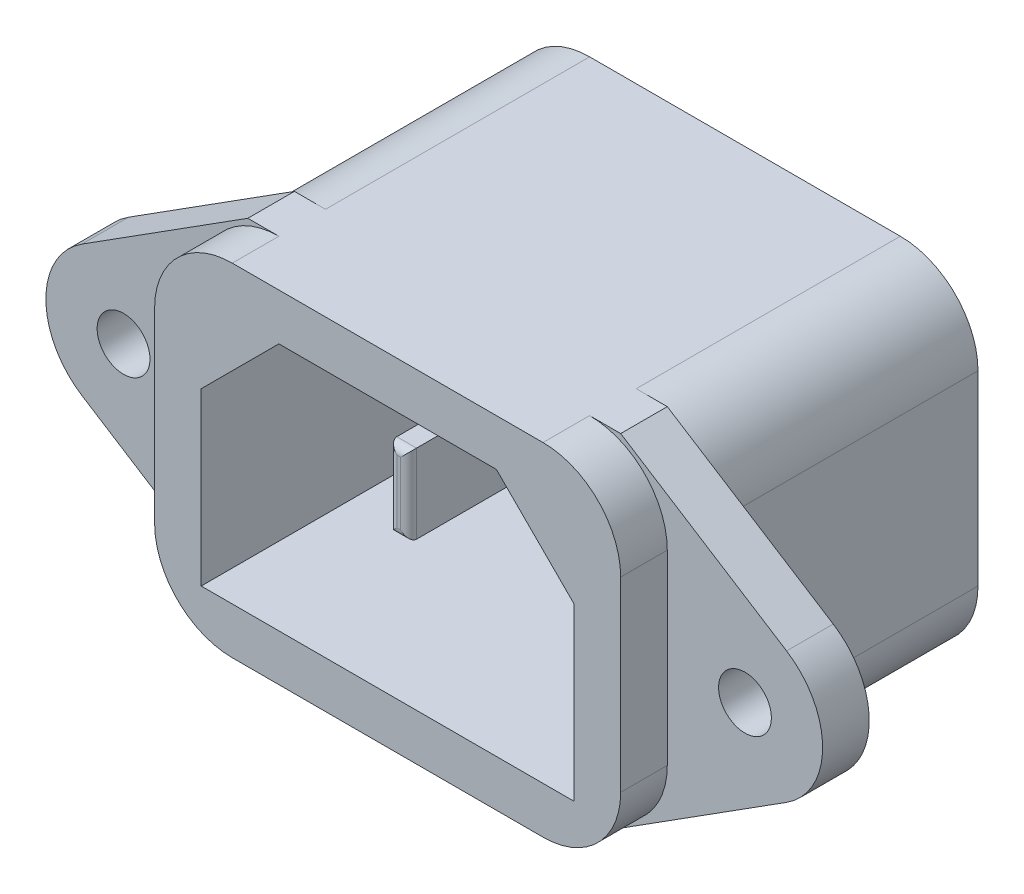
SolidWorks part; units mm, degrees
ref_plane "Front Plane" through (0, 0, 0) normal (0, 0, 1) x (1, 0, 0)
ref_plane "Top Plane" through (0, 0, 0) normal (0, 1, 0) x (1, 0, 0)
ref_plane "Right Plane" through (0, 0, 0) normal (1, 0, 0) x (0, 0, -1)
sketch "Sketch1" plane through (0, 0, 0) normal (0, 0, 1) x (1, 0, 0)
  line L0 (24, 22) -> (34.6795, 15.2214)
  line L1 (0, 0) -> (24, 0)
  line L3 (0, 22) -> (24, 22)
  line L5 (34.6795, 6.7786) -> (24, 0)
  line L6 (0, 22) -> (-10.6795, 15.2214)
  line L7 (-10.6795, 6.7786) -> (0, 0)
  arc A0 (34.6795, 15.2214) -> (34.6795, 6.7786) centre (32, 11) cw
  arc A1 (-10.6795, 15.2214) -> (-10.6795, 6.7786) centre (-8, 11) ccw
  point P9 (41.3302, 11)
  point P12 (-17.3302, 11)
  point P13 (12, 22)
  dimension "D5" = 5
  dimension "D6" = 5
  dimension "D1" = 24
  dimension "D2" = 22
  dimension "D3" = 20
  dimension "D4" = 20
extrude "Boss-Extrude1" add sketch "Sketch1" along normal blind 3
sketch "Sketch2" plane through (0, 0, 3) normal (0, 0, 1) x (1, 0, 0)
  circle A0 centre (32, 11) radius 1.7
  circle A1 centre (-8, 11) radius 1.7
  dimension "D1" = 3.4
  dimension "D2" = 3.4
extrude "Cut-Extrude1" cut sketch "Sketch2" against normal blind 3
sketch "Sketch3" plane through (0, 0, 3) normal (0, 0, 1) x (1, 0, 0)
  line L1 (2, 22) -> (22, 22)
  line L2 (-3, 17) -> (-3, 5)
  line L3 (2, 0) -> (22, 0)
  line L4 (27, 17) -> (27, 5)
  circle A0 centre (32, 11) radius 1.7 construction
  circle A4 centre (-8, 11) radius 1.7 construction
  arc A5 (-3, 5) -> (2, 0) centre (2, 5) ccw
  arc A6 (22, 0) -> (27, 5) centre (22, 5) ccw
  arc A7 (22, 22) -> (27, 17) centre (22, 17) cw
  arc A8 (2, 22) -> (-3, 17) centre (2, 17) ccw
  point P12 (27, 0)
  point P15 (27, 22)
  dimension "D3" = 22
  dimension "D4" = 11
  dimension "D1" = 5
  dimension "D5" = 5
  dimension "D6" = 5
  dimension "D7" = 5
  dimension "D8" = 5
  dimension "D2" = 5
extrude "Boss-Extrude2" add sketch "Sketch3" along normal blind 3 and the other way blind 20
sketch "Sketch5" plane through (0, 0, 6) normal (0, 0, 1) x (1, 0, 0)
  line L0 (22, 22) -> (2, 22) construction
  line L1 (5, 19) -> (19, 19)
  line L2 (0, 14) -> (0, 3)
  line L3 (0, 3) -> (24, 3)
  line L4 (24, 14) -> (24, 3)
  line L5 (-3, 17) -> (-3, 5) construction
  line L6 (5, 19) -> (0, 14)
  line L7 (19, 19) -> (24, 14)
  dimension "D1" = 14
  dimension "D3" = 3
  dimension "D4" = 3
  dimension "D5" = 5
  dimension "D6" = 45
  dimension "D7" = 5
  dimension "D8" = 45
extrude "Cut-Extrude2" cut sketch "Sketch5" against normal blind 17
sketch "Sketch6" plane through (0, 0, -11) normal (0, 0, 1) x (1, 0, 0)
  line L0 (19, 19) -> (5, 19) construction
  line L1 (11.4234, 17.73) -> (12.6934, 17.73)
  line L2 (11.4234, 17.73) -> (11.4234, 12.65)
  line L3 (11.4234, 12.65) -> (12.6934, 12.65)
  line L4 (12.6934, 17.73) -> (12.6934, 12.65)
  line L5 (11.4234, 17.73) -> (12.6934, 12.65) construction
  line L6 (11.4234, 12.65) -> (12.6934, 17.73) construction
  line L7 (17.65, 10.11) -> (18.92, 10.11)
  line L8 (17.65, 10.11) -> (17.65, 5.03)
  line L9 (17.65, 5.03) -> (18.92, 5.03)
  line L10 (18.92, 10.11) -> (18.92, 5.03)
  line L11 (17.65, 10.11) -> (18.92, 5.03) construction
  line L12 (17.65, 5.03) -> (18.92, 10.11) construction
  line L13 (5.08, 10.11) -> (6.35, 10.11)
  line L14 (5.08, 10.11) -> (5.08, 5.03)
  line L15 (5.08, 5.03) -> (6.35, 5.03)
  line L16 (6.35, 10.11) -> (6.35, 5.03)
  line L17 (5.08, 10.11) -> (6.35, 5.03) construction
  line L18 (5.08, 5.03) -> (6.35, 10.11) construction
  line L19 (24, 3) -> (24, 14) construction
  line L20 (0, 14) -> (0, 3) construction
  point P0 (12.0584, 15.19)
  point P5 (18.285, 7.57)
  point P10 (5.715, 7.57)
  dimension "D1" = 1.27
  dimension "D2" = 5.08
  dimension "D3" = 1.27
  dimension "D4" = 1.27
  dimension "D5" = 5.08
  dimension "D6" = 5.08
  dimension "D7" = 2.54
  dimension "D8" = 1.27
  dimension "D9" = 5.08
  dimension "D10" = 5.08
  dimension "D11" = 2.54
extrude "Boss-Extrude3" add sketch "Sketch6" along normal blind 10
fillet "Fillet1" radius 0.508 12 edges at (12.0584, 17.73, -1) (12.0584, 12.65, -1) (5.715, 5.03, -1) (5.715, 10.11, -1) (5.08, 7.57, -1) (6.35, 7.57, -1) (18.285, 5.03, -1) (18.285, 10.11, -1) (17.65, 7.57, -1) (18.92, 7.57, -1) (11.4234, 15.19, -1) (12.6934, 15.19, -1)
